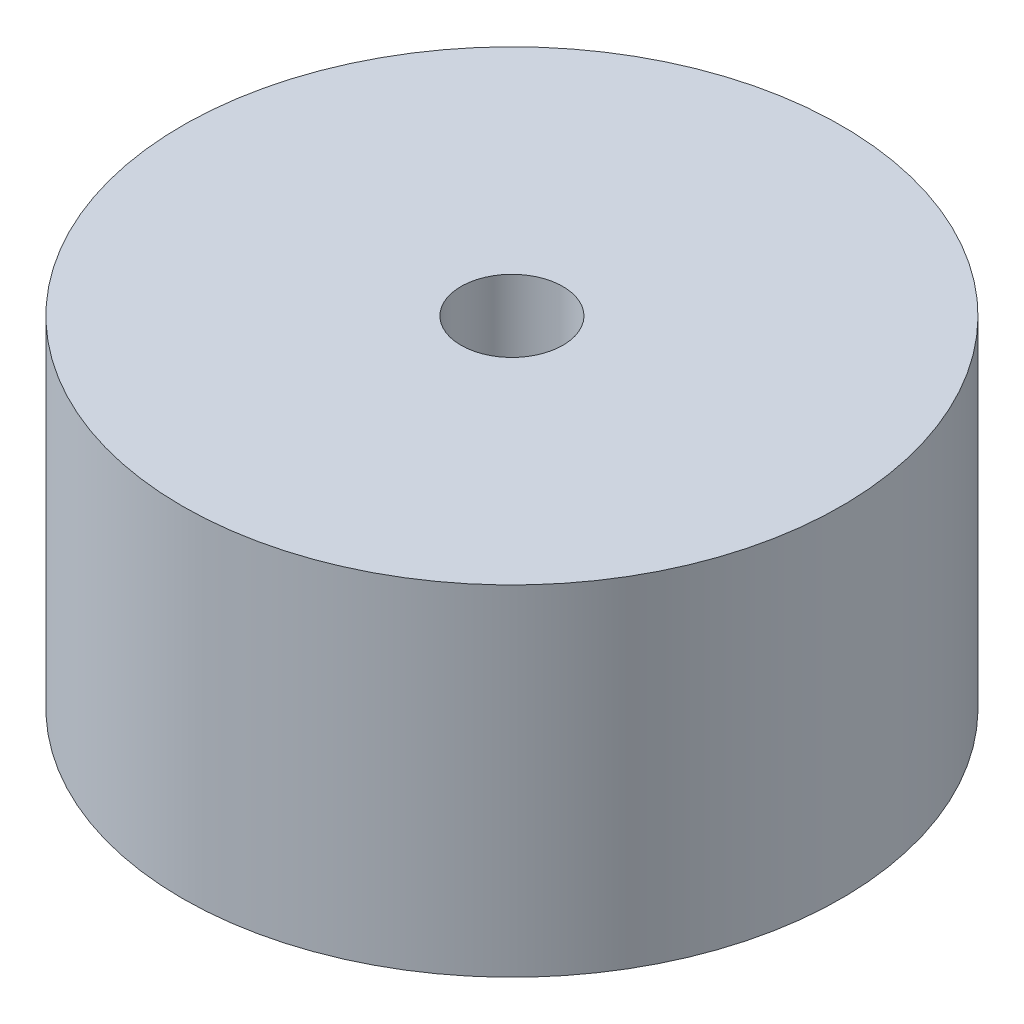
SolidWorks part; units mm, degrees
ref_plane "Front Plane" through (0, 0, 0) normal (0, 0, 1) x (1, 0, 0)
ref_plane "Top Plane" through (0, 0, 0) normal (0, 1, 0) x (1, 0, 0)
ref_plane "Right Plane" through (0, 0, 0) normal (1, 0, 0) x (0, 0, -1)
sketch "Sketch1" plane through (0, 0, 0) normal (0, 1, 0) x (1, 0, 0)
  circle A0 centre (0, 0) radius 48.5
  dimension "D1" = 97
extrude "Boss-Extrude1" add sketch "Sketch1" along normal blind 50
sketch "Sketch2" plane through (0, 50, 0) normal (0, 1, 0) x (1, 0, 0)
  circle A0 centre (0, 0) radius 7.5
  dimension "D1" = 15
extrude "Cut-Extrude1" cut sketch "Sketch2" against normal blind 30
